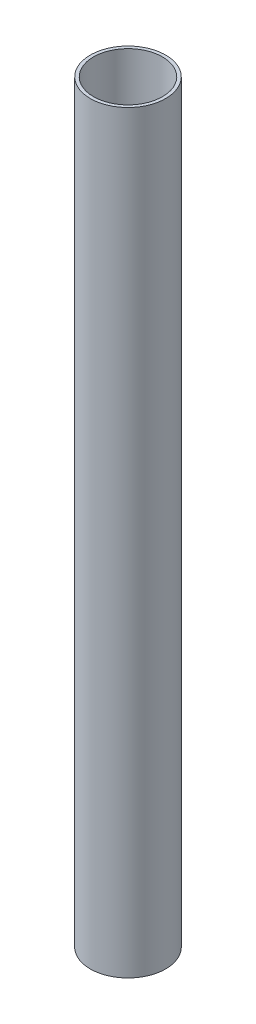
SolidWorks part; units mm, degrees
material "6061 Alloy"
ref_plane "Front Plane" through (0, 0, 0) normal (0, 0, 1) x (1, 0, 0)
ref_plane "Top Plane" through (0, 0, 0) normal (0, 1, 0) x (1, 0, 0)
ref_plane "Right Plane" through (0, 0, 0) normal (1, 0, 0) x (0, 0, -1)
sketch "Sketch1" plane through (0, 0, 0) normal (0, 1, 0) x (1, 0, 0)
  circle A0 centre (0, 0) radius 75
  circle A1 centre (0, 0) radius 68.65
  dimension "D1" = 150
  dimension "D2" = 6.35
extrude "Boss-Extrude1" add sketch "Sketch1" along normal blind 1500
